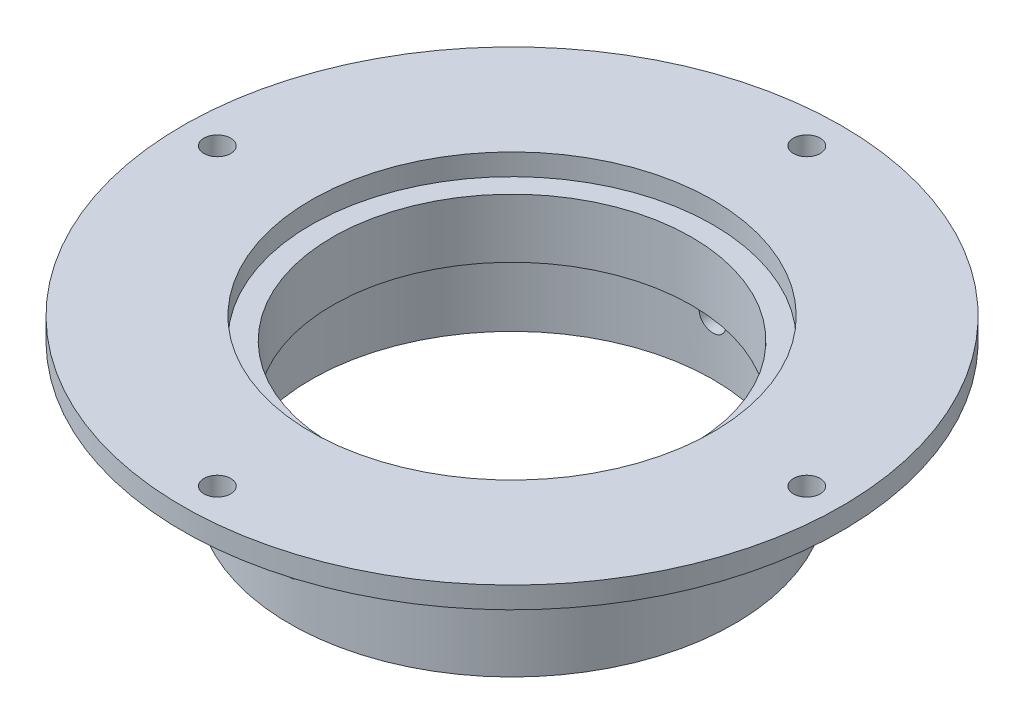
SolidWorks part; units mm, degrees
ref_plane "Front Plane" through (0, 0, 0) normal (0, 0, 1) x (1, 0, 0)
ref_plane "Top Plane" through (0, 0, 0) normal (0, 1, 0) x (1, 0, 0)
ref_plane "Right Plane" through (0, 0, 0) normal (1, 0, 0) x (0, 0, -1)
sketch "Sketch1" plane through (0, 0, 0) normal (0, 0, 1) x (1, 0, 0)
  line L0 (-41.5, -29) -> (-41.5, -4)
  line L25 (-41.5, -4) -> (-61.5, -4)
  line L26 (-61.5, -4) -> (-61.5, 0)
  line L31 (-61.5, 0) -> (-37.5, 0)
  line L32 (-33.5, -4) -> (-33.5, -15)
  line L35 (-33.5, -15) -> (-37.5, -15)
  line L36 (-37.5, -15) -> (-37.5, -29)
  line L37 (-37.5, -29) -> (-41.5, -29)
  line L41 (-33.5, -4) -> (-37.5, -4)
  line L42 (-37.5, 0) -> (-37.5, -4)
  point P3 (0, 0)
  point P4 (0, 0)
  point P5 (0, 0)
  point P6 (0, 0)
  point P7 (0, 0)
  dimension "D2" = 4
  dimension "D3" = 4
  dimension "D5" = 15
  dimension "D6" = 4
  dimension "D9" = 37.5
  dimension "D10" = 25
  dimension "D13" = 20
ref_axis "Axis1" through (0, -100.5, 0) along (0, 1, 0)
revolve "Revolve1" add sketch "Sketch1" angle 360 about axis through (0, -100.5, 0) along (0, 1, 0)
sketch "Sketch2" plane through (0, -4, 0) normal (0, -1, 0) x (1, 0, 0)
  circle A0 centre (55, 0) radius 2.5
  circle A1 centre (-55, 0) radius 2.5
  circle A2 centre (0, 0) radius 61.5 construction
  circle A3 centre (0, 55) radius 2.5
  circle A4 centre (0, -55) radius 2.5
  point P11 (0, 0)
  point P13 (0, 0)
  dimension "D1" = 5
  dimension "D3" = 55
  dimension "D2" = 55
  dimension "D4" = 55
  dimension "D5" = 55
extrude "Cut-Extrude3" cut sketch "Sketch2" against normal through all
sketch "Sketch6" plane through (0, 0, 0) normal (0, 0, 1) x (1, 0, 0)
  line L0 (0, -100.5) -> (0, 20.5) construction
  line L1 (-41.5, -29) -> (41.5, -29) construction
  circle A0 centre (0, -19) radius 2.5
  dimension "D1" = 5
  dimension "D2" = 10
extrude "Cut-Extrude6" cut sketch "Sketch6" against normal through all both and the other way through all
